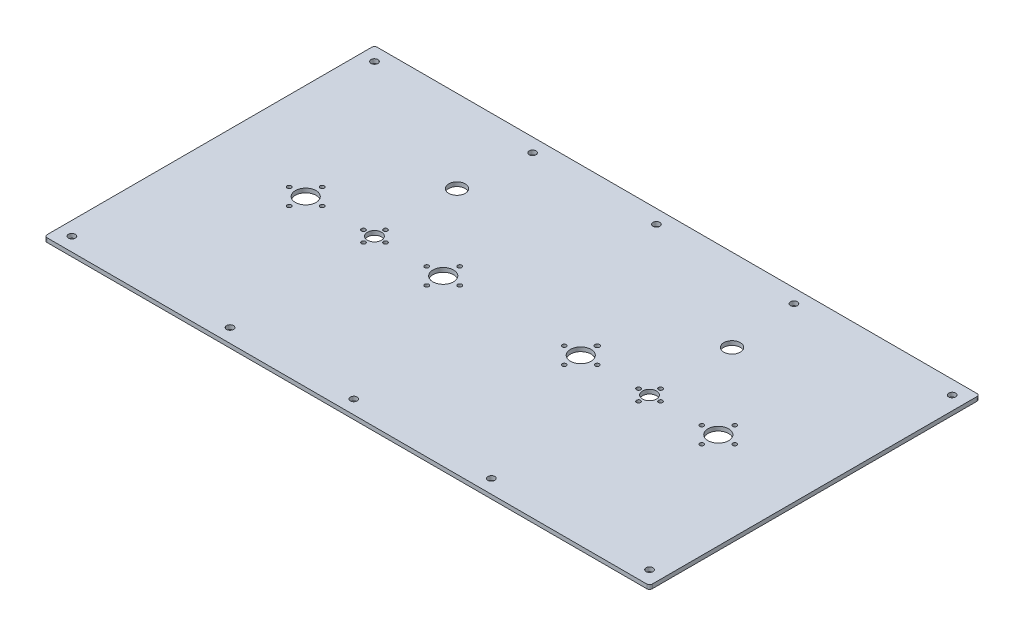
SolidWorks part; units mm, degrees
ref_plane "前视基准面" through (0, 0, 0) normal (0, 0, 1) x (1, 0, 0)
ref_plane "上视基准面" through (0, 0, 0) normal (0, 1, 0) x (1, 0, 0)
ref_plane "右视基准面" through (0, 0, 0) normal (1, 0, 0) x (0, 0, -1)
sketch "草图1" plane through (0, 0, 0) normal (0, 1, 0) x (1, 0, 0)
  line L0 (300, 100) -> (300, 160)
  line L1 (-18, 220) -> (418, 220)
  line L2 (-20, 218) -> (-20, -18)
  line L3 (-18, -20) -> (418, -20)
  line L4 (420, 218) -> (420, -18)
  line L6 (415, -10) -> (322.8759, -10) construction
  line L7 (250, 100) -> (150, 100) construction
  line L8 (415, 210) -> (322.8759, 210) construction
  line L15 (100, 100) -> (100, 160)
  line L33 (100, 100) -> (150, 100)
  circle A0 centre (100, 100) radius 5.1
  circle A1 centre (150, 112) radius 1.5
  circle A2 centre (100, 92) radius 1.5
  circle A3 centre (108, 100) radius 1.5
  circle A4 centre (92, 100) radius 1.5
  circle A5 centre (100, 108) radius 1.5
  circle A6 centre (50, 100) radius 7.5
  circle A7 centre (50, 112) radius 1.5
  circle A8 centre (62, 100) radius 1.5
  circle A9 centre (50, 88) radius 1.5
  circle A10 centre (38, 100) radius 1.5
  circle A11 centre (162, 100) radius 1.5
  circle A12 centre (138, 100) radius 1.5
  circle A13 centre (150, 88) radius 1.5
  circle A14 centre (150, 100) radius 7.5
  circle A15 centre (100, 160) radius 6
  circle A16 centre (300, 100) radius 5.1
  circle A17 centre (350, 112) radius 1.5
  circle A18 centre (300, 108) radius 1.5
  circle A19 centre (308, 100) radius 1.5
  circle A20 centre (300, 92) radius 1.5
  circle A21 centre (292, 100) radius 1.5
  circle A22 centre (250, 100) radius 7.5
  circle A23 centre (250, 112) radius 1.7
  circle A24 centre (262, 100) radius 1.5
  circle A25 centre (250, 88) radius 1.5
  circle A26 centre (238, 100) radius 1.5
  circle A27 centre (362, 100) radius 1.5
  circle A28 centre (338, 100) radius 1.5
  circle A29 centre (350, 88) radius 1.5
  circle A30 centre (350, 100) radius 7.5
  circle A31 centre (300, 160) radius 6
  arc A32 (420, 218) -> (418, 220) centre (418, 218) ccw
  arc A33 (418, -20) -> (420, -18) centre (418, -18) ccw
  arc A34 (-18, -20) -> (-20, -18) centre (-18, -18) cw
  arc A35 (-18, 220) -> (-20, 218) centre (-18, 218) ccw
  circle A36 centre (410, -10) radius 2.5
  circle A37 centre (105, -10) radius 2.5
  circle A38 centre (295, -10) radius 2.5
  circle A39 centre (-10, -10) radius 2.5
  circle A40 centre (195, -10) radius 2.5
  circle A41 centre (195, 210) radius 2.5
  circle A42 centre (-10, 210) radius 2.5
  circle A43 centre (295, 210) radius 2.5
  circle A44 centre (105, 210) radius 2.5
  circle A45 centre (410, 210) radius 2.5
  point P19 (300, 100)
  point P38 (300, 100)
  point P46 (100, 100)
  point P52 (350, 100)
  point P66 (50, 100)
  point P74 (150, 100)
  point P81 (-20, -20)
  point P84 (-20, 220)
  point P111 (100, 100)
  dimension "D2" = 12
  dimension "D3" = 50
  dimension "D4" = 12
  dimension "D7" = 440
  dimension "D15" = 2
  dimension "D16" = 5
  dimension "D19" = 125
  dimension "D20" = 10
  dimension "D21" = 125
  dimension "D22" = 225
  dimension "D23" = 50
  dimension "D24" = 3
  dimension "D25" = 3
  dimension "D26" = 3
  dimension "D27" = 3
  dimension "D28" = 3
  dimension "D29" = 3
  dimension "D30" = 3
  dimension "D31" = 3
  dimension "D32" = 3
  dimension "D1" = 240
  dimension "D8" = 120
  dimension "D9" = 120
  dimension "D10" = 50
  dimension "D11" = 12
  dimension "D12" = 12
  dimension "D13" = 120
  dimension "D14" = 120
  dimension "D17" = 10
  dimension "D18" = 10
  dimension "D33" = 4
  dimension "D5" = 4
  dimension "D6" = 4
extrude "凸台-拉伸1" add sketch "草图1" along normal blind 3
